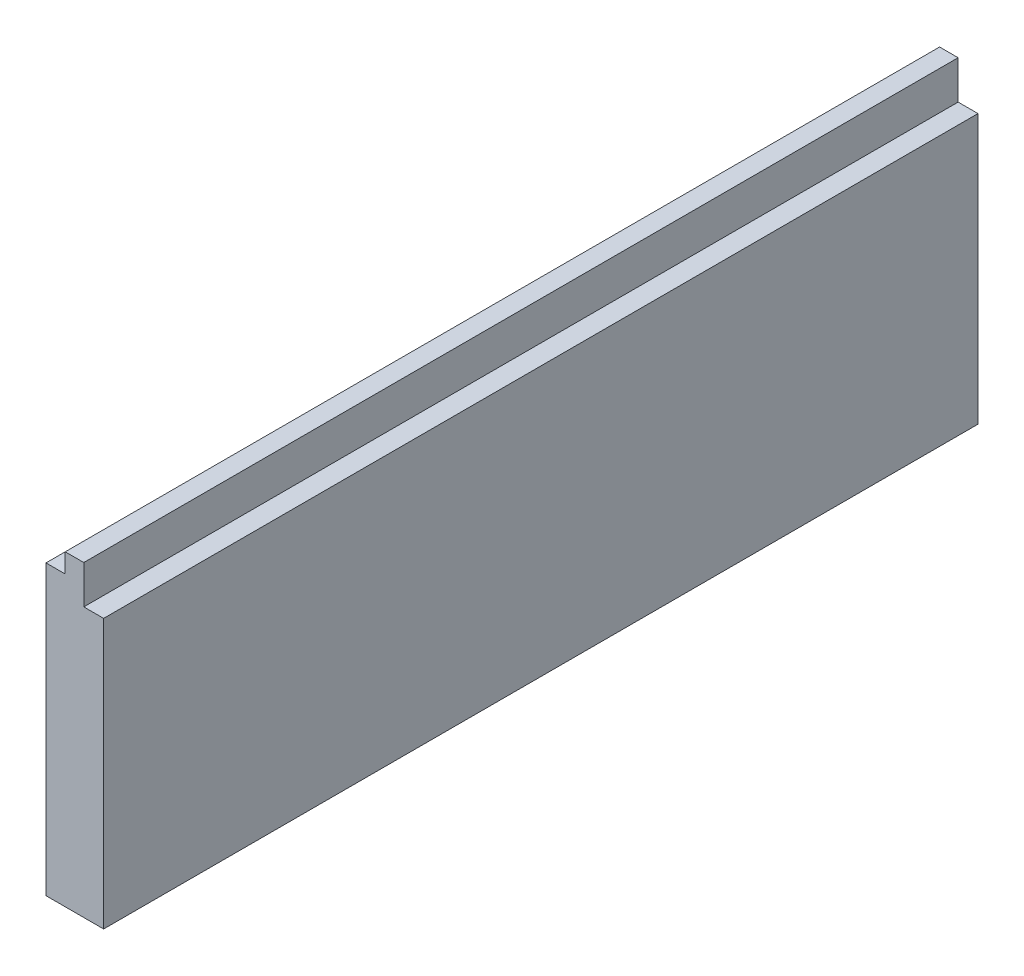
SolidWorks part; units mm, degrees
material "Сосна"
ref_plane "Спереди" through (0, 0, 0) normal (0, 0, 1) x (1, 0, 0)
ref_plane "Сверху" through (0, 0, 0) normal (0, 1, 0) x (1, 0, 0)
ref_plane "Справа" through (0, 0, 0) normal (1, 0, 0) x (0, 0, -1)
sketch "Эскиз1" plane through (0, 0, 0) normal (0, 0, 1) x (1, 0, 0)
  line L0 (0, 0) -> (10, 0)
  line L2 (10, 0) -> (30, 0)
  line L3 (30, 0) -> (30, 140)
  line L4 (30, 140) -> (19.6619, 140)
  line L5 (10, 160) -> (10, 150)
  line L6 (10, 150) -> (0, 150)
  line L7 (0, 150) -> (0, 0)
  line L8 (19.6619, 160) -> (10, 160)
  line L9 (19.6619, 140) -> (19.6619, 160)
  dimension "D1" = 150
  dimension "D2" = 30
  dimension "D3" = 10
  dimension "D4" = 20
  dimension "D5" = 10
extrude "Бобышка-Вытянуть1" add sketch "Эскиз1" along normal blind 455
